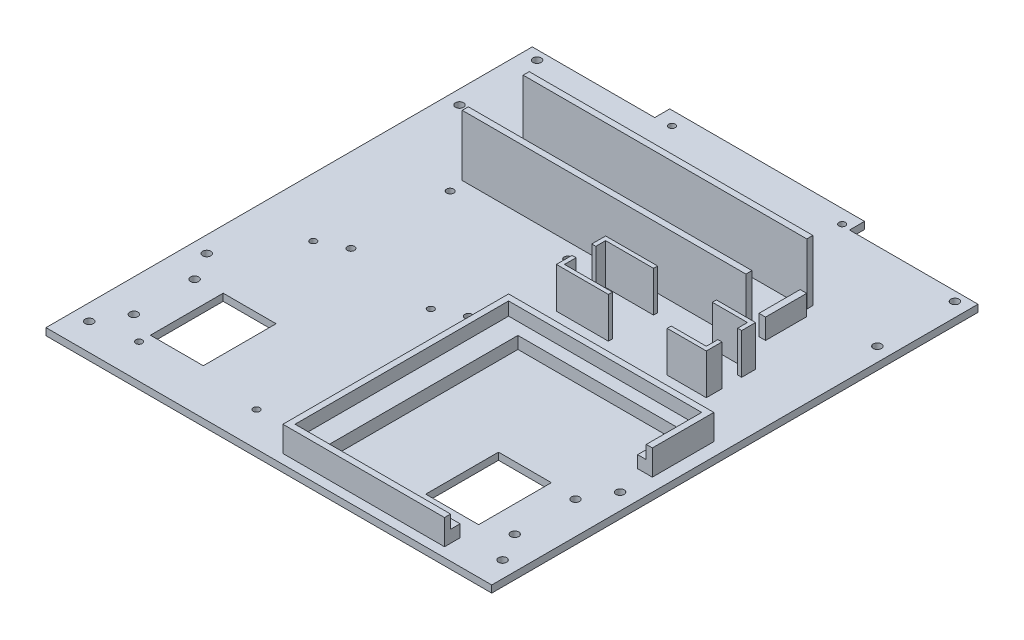
SolidWorks part; units mm, degrees
ref_plane "前视基准面" through (0, 0, 0) normal (0, 0, 1) x (1, 0, 0)
ref_plane "上视基准面" through (0, 0, 0) normal (0, 1, 0) x (1, 0, 0)
ref_plane "右视基准面" through (0, 0, 0) normal (1, 0, 0) x (0, 0, -1)
other "Configuration Table"
sketch "草图1" plane through (0, 0, 0) normal (0, 1, 0) x (1, 0, 0)
  line L0 (-110, 140) -> (-110, -100)
  line L7 (110, 140) -> (-110, 140)
  line L9 (-110, -100) -> (110, -100)
  line L10 (110, -100) -> (110, 140)
  point P0 (0, 0)
  dimension "D1" = 220
  dimension "D2" = 240
extrude "凸台-拉伸2" add sketch "草图1" along normal blind 3.5
sketch "草图2" plane through (0, 3.5, 0) normal (0, 1, 0) x (1, 0, 0)
  line L2 (-94, -44.6583) -> (-94, -42.6583)
  line L3 (-94, -70.6583) -> (-94, -72.6583)
  line L5 (94, -70.6583) -> (94, -72.6583)
  line L6 (94, -44.6583) -> (94, -42.6583)
  circle A8 centre (-102, -28.6583) radius 2
  circle A9 centre (-102, -86.6583) radius 2
  circle A10 centre (-94, -42.6583) radius 2
  circle A11 centre (-94, -72.6583) radius 2
  circle A12 centre (94, -72.6583) radius 2
  circle A13 centre (94, -42.6583) radius 2
  circle A14 centre (102, -86.6583) radius 2
  circle A15 centre (102, -28.6583) radius 2
  point P3 (0, 0)
  dimension "D3" = 4
  dimension "D4" = 4
  dimension "D5" = 4
  dimension "D2" = 4
  dimension "D1" = 58
extrude "切除-拉伸2" cut sketch "草图2" against normal blind 3.5 contours A8 | A10 | A11 | A9 | A14 | A12 | A13 | A15
sketch "草图3" plane through (0, 3.5, 0) normal (0, 1, 0) x (1, 0, 0)
  line L0 (-103.1118, 135.4984) -> (-103.1118, 99.1984)
  line L1 (0, 140) -> (0, 133.5773)
  line L2 (110, 140) -> (-110, 140) construction
  circle A0 centre (-103.1118, 135.4984) radius 2
  circle A2 centre (-103.1118, 97.1984) radius 2
  circle A4 centre (103.1118, 97.1984) radius 2
  circle A5 centre (103.1118, 135.4984) radius 2
  dimension "D2" = 4
  dimension "D3" = 4
  dimension "D1" = 38.3
extrude "切除-拉伸3" cut sketch "草图3" against normal blind 3.5 contours A0 | A2 | A5 | A4
sketch "草图4" plane through (0, 3.5, 0) normal (0, 1, 0) x (1, 0, 0)
  line L1 (5.2625, 13.0615) -> (100.5625, 13.0615)
  line L2 (5.2625, 13.0615) -> (5.2625, -92.3385)
  line L3 (5.2625, -92.3385) -> (100.5625, -92.3385)
  line L4 (100.5625, 13.0615) -> (100.5625, -92.3385)
  line L9 (-19.0684, -89.6377) -> (-99.0684, -89.6377)
  line L10 (-19.0684, -89.6377) -> (-19.0684, 10.3623)
  line L11 (-19.0684, 10.3623) -> (-99.0684, 10.3623)
  line L12 (-99.0684, -89.6377) -> (-99.0684, 10.3623)
  line L15 (-23.0207, -83.0539) -> (-81.0207, -83.0539)
  line L16 (-23.0207, -83.0539) -> (-23.0207, 2.9461)
  line L17 (-23.0207, 2.9461) -> (-81.0207, 2.9461)
  line L18 (-81.0207, -83.0539) -> (-81.0207, 2.9461)
  line L20 (-54.1357, -45.8035) -> (-56.6476, -49.528) construction
  circle A6 centre (-81.0207, 2.9461) radius 1.6
  circle A7 centre (-23.0207, 2.9461) radius 1.6
  circle A8 centre (-81.0207, -83.0539) radius 1.6
  circle A9 centre (-23.0207, -83.0539) radius 1.6
  point P4 (-59.0684, -39.6377)
  point P5 (-92.581, -35.2846)
  point P10 (-56.6476, -49.528)
  dimension "D3" = 80
  dimension "D4" = 100
  dimension "D5" = 58
  dimension "D7" = 3.2
  dimension "D8" = 3.2
  dimension "D9" = 3.2
  dimension "D10" = 3.2
  dimension "D1" = 95.3
  dimension "D2" = 105.4
  dimension "D6" = 86
sketch "草图5" plane through (0, 3.5, 0) normal (0, 1, 0) x (1, 0, 0)
  circle A0 centre (-81.0207, 2.9461) radius 1.6
  circle A1 centre (-23.0207, 2.9461) radius 1.6
  circle A2 centre (-81.0207, -83.0539) radius 1.6
  circle A3 centre (-23.0207, -83.0539) radius 1.6
extrude "切除-拉伸4" cut sketch "草图5" against normal blind 5
sketch "草图6" plane through (0, 3.5, 0) normal (0, 1, 0) x (1, 0, 0)
  line L0 (5.2625, 13.0615) -> (5.2625, -92.3385)
  line L1 (5.2625, -92.3385) -> (82.0277, -92.3385)
  line L2 (100.5625, -14.3045) -> (100.5625, 13.0615)
  line L3 (100.5625, 13.0615) -> (5.2625, 13.0615)
  line L4 (100.5625, -14.3045) -> (96.3123, -14.3045)
  line L5 (82.0277, -87.6749) -> (82.0277, -92.3385)
  line L6 (15.7995, 7.1223) -> (15.7995, -87.6749)
  line L8 (18.6132, 7.1223) -> (82.0277, 7.1223)
  line L10 (18.6132, 7.1223) -> (15.7995, 7.1223)
  line L12 (15.7995, -87.6749) -> (82.0277, -87.6749)
  line L13 (82.0277, 7.1223) -> (96.3123, 7.1223)
  line L14 (96.3123, 7.1223) -> (96.3123, -14.3045)
extrude "凸台-拉伸5" add sketch "草图6" along normal blind 6
sketch "草图9" plane through (0, 9.5, 0) normal (0, 1, 0) x (1, 0, 0)
  line L0 (5.2625, 13.0615) -> (5.2625, -92.3385)
  line L1 (5.2625, -92.3385) -> (82.0277, -92.3385)
  line L2 (82.0277, -92.3385) -> (82.0277, -87.6749)
  line L3 (82.0277, -87.6749) -> (15.7995, -87.6749)
  line L4 (15.7995, -87.6749) -> (15.7995, 7.1223)
  line L5 (15.7995, 7.1223) -> (96.3123, 7.1223)
  line L6 (96.3123, 7.1223) -> (96.3123, -14.3045)
  line L7 (96.3123, -14.3045) -> (100.5625, -14.3045)
  line L8 (100.5625, -14.3045) -> (100.5625, 13.0615)
  line L9 (100.5625, 13.0615) -> (5.2625, 13.0615)
  line L10 (103.5625, 16.0615) -> (2.2625, 16.0615)
  line L11 (2.2625, 16.0615) -> (2.2625, -95.3385)
  line L12 (2.2625, -95.3385) -> (82.0277, -95.3385)
  line L19 (103.5625, -14.3045) -> (103.5625, 16.0615)
  line L20 (18.7995, 4.1223) -> (93.3123, 4.1223) construction
  line L21 (18.7995, -84.6749) -> (18.7995, 4.1223) construction
  line L22 (85.0277, -84.6749) -> (18.7995, -84.6749) construction
  line L23 (85.0277, -95.3385) -> (85.0277, -84.6749) construction
  line L24 (93.3123, 4.1223) -> (93.3123, -17.3045) construction
  line L25 (93.3123, -17.3045) -> (103.5625, -17.3045) construction
  line L26 (82.0277, -92.3385) -> (82.0277, -95.3385)
  line L27 (2.2625, -95.3385) -> (85.0277, -95.3385) construction
  line L28 (100.5625, -14.3045) -> (103.5625, -14.3045)
  line L29 (103.5625, -17.3045) -> (103.5625, 16.0615) construction
  line M11 (100.5625, 13.0615) -> (5.2625, 13.0615)
  line M12 (5.2625, 13.0615) -> (5.2625, -92.3385)
  line M13 (5.2625, -92.3385) -> (82.0277, -92.3385)
  line M20 (100.5625, -14.3045) -> (100.5625, 13.0615)
  dimension "D1" = 3
extrude "凸台-拉伸6" add sketch "草图9" along normal blind 6.5 and the other way blind 6.6 contours L28 L19 L10 L11 L12 L26 M20 M13 M12 M11
sketch "草图10" plane through (0, 3.5, 0) normal (0, 1, 0) x (1, 0, 0)
  line L1 (0.2576, 136.3159) -> (0, 136.3159)
  line L5 (0, 140) -> (0, 135.8367)
  line L6 (110, 140) -> (-110, 140) construction
  circle A0 centre (-41.7424, 136.3159) radius 1.6
  circle A1 centre (-41.7424, 106.0159) radius 1.6
  circle A2 centre (42.2576, 106.0159) radius 1.6
  circle A3 centre (42.2576, 136.3159) radius 1.6
  dimension "D4" = 3.2
  dimension "D5" = 3.2
  dimension "D6" = 3.2
  dimension "D7" = 3.2
  dimension "D1" = 42
  dimension "D2" = 42
  dimension "D3" = 30.3
extrude "切除-拉伸5" cut sketch "草图10" against normal blind 6.5 contours A0 | A3 | A2 | A1
sketch "草图11" plane through (0, 3.5, 0) normal (0, 1, 0) x (1, 0, 0)
  line L0 (0, 82.1303) -> (0, 82.1921)
  line L5 (-70.1602, 95.6612) -> (69.8398, 95.6612)
  line L9 (-0.1602, 82.1612) -> (0, 82.1303) construction
  line L10 (-0.1602, 82.1612) -> (0, 82.1921) construction
  line L11 (0, 95.6612) -> (0, 95.9857)
  line L12 (-70.1602, 95.6612) -> (-70.1602, 98.6612)
  line L13 (-70.1602, 98.6612) -> (69.8398, 98.6612)
  line L14 (69.8398, 98.6612) -> (69.8398, 95.6612)
  line L15 (0, 82.1303) -> (13.8264, 82.1303)
  line L16 (69.8398, 65.5994) -> (69.8398, 68.5994)
  line L17 (-70.1602, 68.5994) -> (-70.1602, 65.5994)
  line L18 (-70.1602, 65.5994) -> (69.8398, 65.5994)
  line L19 (-70.1602, 68.5994) -> (69.8398, 68.5994)
  point P0 (-38.8338, 65.6942)
  point P1 (-0.1602, 82.1612)
  dimension "D1" = 140
  dimension "D3" = 3
extrude "凸台-拉伸7" add sketch "草图11" along normal blind 30
sketch "草图12" plane through (0, 3.5, 0) normal (0, 1, 0) x (1, 0, 0)
  line L0 (69.8398, 92.3659) -> (69.8398, 72.0668)
  line L1 (69.8398, 92.3659) -> (73.0722, 92.3659)
  line L2 (73.0722, 92.3659) -> (73.0722, 72.0668)
  line L3 (73.0722, 72.0668) -> (69.8398, 72.0668)
extrude "凸台-拉伸8" add sketch "草图12" along normal blind 10
sketch "草图13" plane through (0, 3.5, 0) normal (0, 1, 0) x (1, 0, 0)
  line L1 (-70.8174, 88.5623) -> (-70.8174, 76.9107)
  line L2 (-70.8174, 76.9107) -> (-73.5822, 76.9107)
  line L3 (-73.5822, 76.9107) -> (-73.5822, 88.5623)
  line L4 (-73.5822, 88.5623) -> (-70.8174, 88.5623)
extrude "凸台-拉伸9" add sketch "草图13" along normal blind 10
sketch "草图14" plane through (0, 33.5, 0) normal (0, 1, 0) x (1, 0, 0)
  line L1 (-41.7424, 136.3159) -> (-41.7424, 110.389)
  line L2 (-41.7424, 110.389) -> (42.2576, 110.389)
  line L3 (42.2576, 110.389) -> (42.2576, 136.3159)
  line L4 (-41.7424, 110.389) -> (-41.7424, 140.689)
  line L5 (-41.7424, 140.689) -> (42.2576, 140.689)
  line L6 (42.2576, 140.689) -> (42.2576, 136.3159)
  dimension "D1" = 30.3
sketch "草图16" plane through (0, 3.5, 0) normal (0, 1, 0) x (1, 0, 0)
  line L0 (-49.5605, 140) -> (-49.5605, 147.416)
  line L1 (110, 140) -> (-110, 140) construction
  line L2 (-49.5605, 147.416) -> (46.5774, 147.416)
  line L3 (46.5774, 147.416) -> (46.5774, 140)
  line L4 (-49.5605, 140) -> (46.5774, 140)
extrude "凸台-拉伸10" add sketch "草图16" against normal up to surface (3.5 mm away) up to face at (-41.7424, 0, -104.4159)
sketch "草图17" plane through (0, 3.5, 0) normal (0, 1, 0) x (1, 0, 0)
  circle A0 centre (-41.7424, 136.3159) radius 1.6
  circle A1 centre (-41.7424, 106.0159) radius 1.6
  circle A2 centre (42.2576, 106.0159) radius 1.6
  circle A3 centre (42.2576, 136.3159) radius 1.6
extrude "凸台-拉伸11" add sketch "草图17" against normal up to surface (3.5 mm away) contours A0 | A1 | A3 | A2 up to face at (-41.7424, 0, -104.4159)
sketch "草图18" plane through (0, 3.5, 0) normal (0, 1, 0) x (1, 0, 0)
  circle A0 centre (-41.7424, 140.689) radius 1.6
  circle A1 centre (-41.7424, 110.389) radius 1.6
  circle A2 centre (42.2576, 110.389) radius 1.6
  circle A3 centre (42.2576, 140.689) radius 1.6
  dimension "D1" = 3.2
  dimension "D2" = 3.2
  dimension "D3" = 3.2
  dimension "D4" = 3.2
extrude "切除-拉伸7" cut sketch "草图18" against normal blind 10
sketch "草图19" plane through (0, 3.5, 0) normal (0, 1, 0) x (1, 0, 0)
  line L0 (-10.6099, 58.1009) -> (-10.6099, 9.1009)
  line L1 (-10.6099, 9.1009) -> (-68.6099, 9.1009)
  line L2 (-10.6099, 58.1009) -> (-68.6099, 58.1009)
  line L3 (-68.6099, 58.1009) -> (-68.6099, 9.1009)
  circle A0 centre (-10.6099, 58.1009) radius 1.75
  circle A2 centre (-68.6099, 58.1009) radius 1.75
  circle A3 centre (-68.6099, 9.1009) radius 1.75
  circle A4 centre (-10.6099, 9.1009) radius 1.75
  dimension "D3" = 3.5
  dimension "D4" = 3.5
  dimension "D5" = 3.5
  dimension "D6" = 3.5
  dimension "D1" = 49
  dimension "D2" = 58
extrude "切除-拉伸8" cut sketch "草图19" against normal blind 10 contours A2 | A3 | A4 | A0
sketch "草图20" plane through (0, 3.5, 0) normal (0, 1, 0) x (1, 0, 0)
  line L0 (82.9329, 32.9755) -> (82.9329, 57.2755)
  line L1 (80.9329, 34.9755) -> (10.9329, 34.9755)
  line L2 (80.9329, 34.9755) -> (80.9329, 55.2755)
  line L3 (80.9329, 55.2755) -> (10.9329, 55.2755)
  line L4 (10.9329, 34.9755) -> (10.9329, 55.2755)
  line L5 (82.9329, 57.2755) -> (8.9329, 57.2755)
  line L6 (8.9329, 32.9755) -> (8.9329, 57.2755)
  line L7 (82.9329, 32.9755) -> (8.9329, 32.9755)
  point P0 (45.9329, 45.1255)
  dimension "D1" = 20.3
  dimension "D2" = 70
  dimension "D3" = 2
extrude "凸台-拉伸12" add sketch "草图20" along normal blind 20
sketch "草图21" plane through (0, 23.5, 0) normal (0, 1, 0) x (1, 0, 0)
  line L0 (8.9329, 50.4308) -> (82.9329, 50.4308)
  line L1 (8.9329, 57.2755) -> (8.9329, 32.9755) construction
  line L2 (82.9329, 32.9755) -> (82.9329, 57.2755) construction
  line L3 (82.9329, 50.4308) -> (82.9329, 40.6891)
  line L4 (82.9329, 40.6891) -> (8.9329, 40.6891)
  line L5 (8.9329, 40.6891) -> (8.9329, 50.4308)
extrude "切除-拉伸9" cut sketch "草图21" against normal blind 20
sketch "草图22" plane through (0, 23.5, 0) normal (0, 1, 0) x (1, 0, 0)
  line L0 (34.599, 57.2755) -> (34.599, 32.9755)
  line L1 (82.9329, 57.2755) -> (8.9329, 57.2755) construction
  line L2 (8.9329, 32.9755) -> (82.9329, 32.9755) construction
  line L3 (34.599, 32.9755) -> (63.61, 32.9755)
  line L4 (63.61, 32.9755) -> (63.61, 57.2755)
  line L5 (63.61, 57.2755) -> (34.599, 57.2755)
extrude "切除-拉伸10" cut sketch "草图22" against normal blind 20
sketch "草图23" plane through (0, 3.5, 0) normal (0, 1, 0) x (1, 0, 0)
  line L0 (-80.9925, -41.5545) -> (-80.9925, -77.4768)
  line L1 (-80.9925, -77.4768) -> (-54.8875, -77.4768)
  line L2 (-54.8875, -77.4768) -> (-54.8875, -41.5545)
  line L3 (-54.8875, -41.5545) -> (-80.9925, -41.5545)
  line L6 (54.8875, -77.4768) -> (54.8875, -41.5545)
  line L7 (80.9925, -77.4768) -> (54.8875, -77.4768)
  line L8 (80.9925, -41.5545) -> (80.9925, -77.4768)
  line L9 (54.8875, -41.5545) -> (80.9925, -41.5545)
extrude "切除-拉伸11" cut sketch "草图23" against normal blind 20
